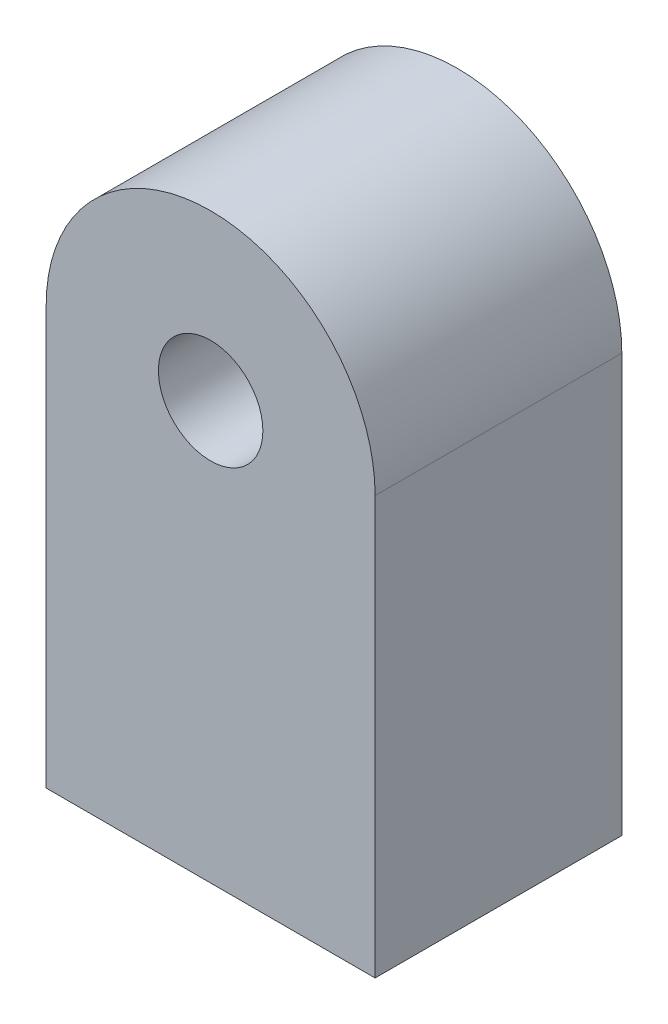
SolidWorks part; units mm, degrees
ref_plane "Front Plane" through (0, 0, 0) normal (0, 0, 1) x (1, 0, 0)
ref_plane "Top Plane" through (0, 0, 0) normal (0, 1, 0) x (1, 0, 0)
ref_plane "Right Plane" through (0, 0, 0) normal (1, 0, 0) x (0, 0, -1)
sketch "Sketch1" plane through (0, 0, 0) normal (0, 0, 1) x (1, 0, 0)
  line L2 (-10, 0) -> (-10, -25.4)
  line L3 (-10, -25.4) -> (10, -25.4)
  line L4 (10, 0) -> (10, -25.4)
  arc A0 (10, 0) -> (-10, 0) centre (0, 0) ccw
  circle A1 centre (0, 0) radius 3.175
  dimension "D1" = 10
  dimension "D3" = 6.35
  dimension "D2" = 25.4
extrude "Boss-Extrude1" add sketch "Sketch1" along normal blind 15
sketch "Sketch2" plane through (0, -25.4, 0) normal (0, -1, 0) x (1, 0, 0)
  line L0 (-10, 15) -> (10, 0) construction
  circle A0 centre (0, 7.5) radius 3.175
  dimension "D1" = 6.35
extrude "Cut-Extrude1" cut sketch "Sketch2" against normal blind 15
